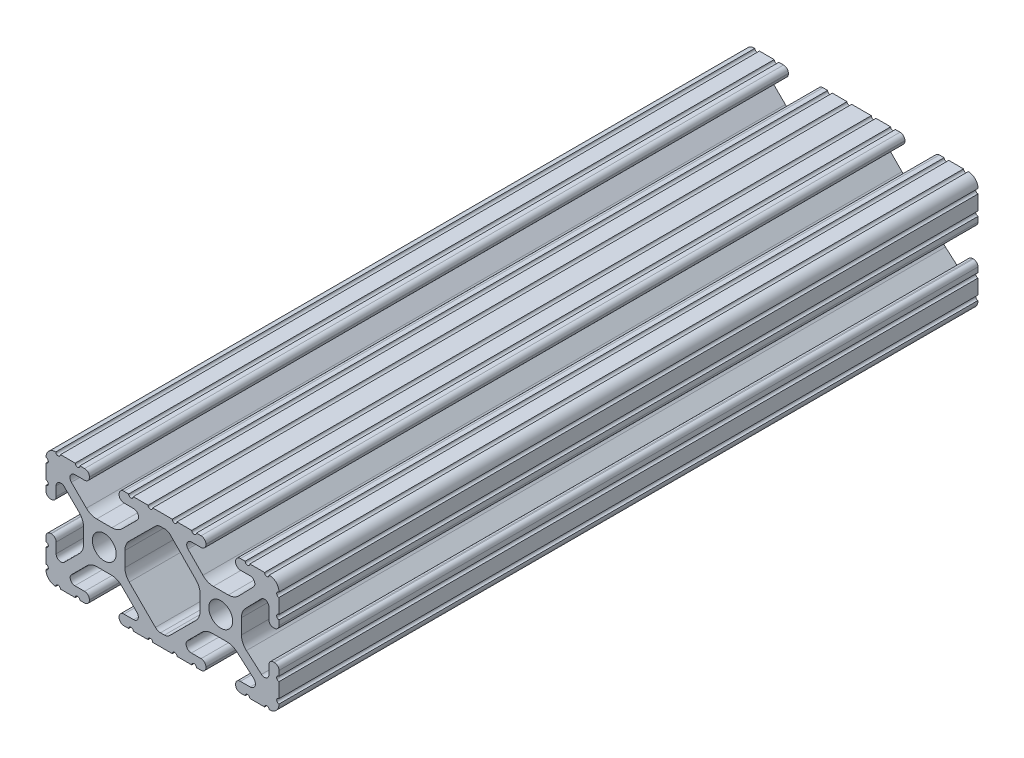
SolidWorks part; units mm, degrees
material "6061-T6 (SS)"
ref_plane "Front Plane" through (0, 0, 0) normal (0, 0, 1) x (1, 0, 0)
ref_plane "Top Plane" through (0, 0, 0) normal (0, 1, 0) x (1, 0, 0)
ref_plane "Right Plane" through (0, 0, 0) normal (1, 0, 0) x (0, 0, -1)
sketch "Sketch1" plane through (0, 0, 0) normal (0, 0, 1) x (1, 0, 0)
  line L0 (-7.2595, -3.8694) -> (-1.5457, -9.5728)
  line L1 (-8.1915, 1.6223) -> (-8.1915, -1.6223)
  line L2 (-1.504, 9.5765) -> (-7.252, 3.8768)
  line L3 (0.5515, 10.033) -> (-0.3952, 10.033)
  line L4 (7.2829, 3.8459) -> (1.6756, 9.5611)
  line L5 (8.1915, -1.6223) -> (8.1915, 1.6223)
  line L6 (1.5457, -9.5728) -> (7.2595, -3.8694)
  line L7 (-0.4332, -10.033) -> (0.4332, -10.033)
  line L8 (18.0171, 12.7) -> (16.9875, 12.7)
  line L9 (15.9385, 11.651) -> (15.9385, 11.5392)
  line L10 (16.9875, 10.4902) -> (19.1164, 10.4902)
  line L11 (19.8441, 8.7652) -> (16.619, 5.4551)
  line L12 (14.3449, 4.4958) -> (11.0833, 4.4958)
  line L13 (8.817, 5.4472) -> (5.5642, 8.7627)
  line L14 (6.2894, 10.4902) -> (8.4125, 10.4902)
  line L15 (9.4615, 11.5392) -> (9.4615, 11.651)
  line L16 (8.4125, 12.7) -> (7.3829, 12.7)
  line L17 (6.3669, 12.7) -> (3.1496, 12.7)
  line L18 (2.1336, 12.7) -> (-2.1336, 12.7)
  line L19 (-3.1496, 12.7) -> (-6.3669, 12.7)
  line L20 (-7.3829, 12.7) -> (-8.4125, 12.7)
  line L21 (-9.4615, 11.651) -> (-9.4615, 11.5392)
  line L22 (-8.4125, 10.4902) -> (-6.2836, 10.4902)
  line L23 (-5.5326, 8.6661) -> (-8.81, 5.4163)
  line L24 (-11.0455, 4.4958) -> (-14.3545, 4.4958)
  line L25 (-16.59, 5.4163) -> (-19.8674, 8.6661)
  line L26 (-19.1164, 10.4902) -> (-16.9875, 10.4902)
  line L27 (-15.9385, 11.5392) -> (-15.9385, 11.651)
  line L28 (-16.9875, 12.7) -> (-18.0171, 12.7)
  line L29 (-19.0331, 12.7) -> (-22.2504, 12.7)
  line L30 (-25.4, 9.5504) -> (-25.4, 6.3331)
  line L31 (-25.4, 5.3171) -> (-25.4, 4.2375)
  line L32 (-24.401, 3.2385) -> (-24.2392, 3.2385)
  line L33 (-23.1902, 4.2875) -> (-23.1902, 6.3347)
  line L34 (-21.434, 7.0665) -> (-18.148, 3.8082)
  line L35 (-17.2085, 1.5536) -> (-17.2085, -1.6952)
  line L36 (-18.1405, -3.9423) -> (-21.4316, -7.2274)
  line L37 (-23.1902, -6.498) -> (-23.1902, -4.2875)
  line L38 (-24.2392, -3.2385) -> (-24.351, -3.2385)
  line L39 (-25.4, -4.2875) -> (-25.4, -5.3171)
  line L40 (-25.4, -6.3331) -> (-25.4, -9.5504)
  line L41 (-22.2504, -12.7) -> (-19.0331, -12.7)
  line L42 (-18.0171, -12.7) -> (-16.9875, -12.7)
  line L43 (-15.9384, -11.651) -> (-15.9384, -11.5392)
  line L44 (-16.9875, -10.4902) -> (-19.1164, -10.4902)
  line L45 (-19.8341, -8.7551) -> (-16.4966, -5.4237)
  line L46 (-14.2536, -4.4958) -> (-11.1464, -4.4958)
  line L47 (-8.9034, -5.4237) -> (-5.5659, -8.7551)
  line L48 (-6.2836, -10.4902) -> (-8.4125, -10.4902)
  line L49 (-9.4616, -11.5392) -> (-9.4616, -11.651)
  line L50 (-8.4125, -12.7) -> (-7.3829, -12.7)
  line L51 (-6.3669, -12.7) -> (-3.1496, -12.7)
  line L52 (-2.1336, -12.7) -> (2.1336, -12.7)
  line L53 (3.1496, -12.7) -> (6.3669, -12.7)
  line L54 (7.3829, -12.7) -> (8.4125, -12.7)
  line L55 (9.4616, -11.651) -> (9.4616, -11.5392)
  line L56 (8.4125, -10.4902) -> (6.2894, -10.4902)
  line L57 (5.4807, -8.5353) -> (8.5979, -5.4237)
  line L58 (10.8409, -4.4958) -> (14.1026, -4.4958)
  line L59 (16.1879, -5.2766) -> (19.8682, -8.4822)
  line L60 (19.1164, -10.4902) -> (16.9875, -10.4902)
  line L61 (15.9384, -11.5392) -> (15.9384, -11.651)
  line L62 (16.9875, -12.7) -> (18.0171, -12.7)
  line L63 (19.0331, -12.7) -> (22.2504, -12.7)
  line L64 (25.4, -9.5504) -> (25.4, -6.3331)
  line L65 (25.4, -5.3171) -> (25.4, -4.2375)
  line L66 (24.401, -3.2385) -> (24.1892, -3.2385)
  line L67 (23.1902, -4.2375) -> (23.1902, -6.1559)
  line L68 (21.584, -6.8869) -> (18.2982, -4.025)
  line L69 (17.2085, -1.6308) -> (17.2085, 1.6308)
  line L70 (18.1094, 3.8465) -> (21.5263, 7.3534)
  line L71 (23.1902, 6.6769) -> (23.1902, 4.2375)
  line L72 (24.1892, 3.2385) -> (24.401, 3.2385)
  line L73 (25.4, 4.2375) -> (25.4, 5.3171)
  line L74 (25.4, 6.3332) -> (25.4, 9.5504)
  line L75 (22.2504, 12.7) -> (19.0331, 12.7)
  circle A0 centre (-12.7, 0) radius 2.6035
  circle A1 centre (12.7, 0) radius 2.6035
  arc A2 (-1.5457, -9.5728) -> (-0.4332, -10.033) centre (-0.4332, -8.4582) ccw
  arc A3 (-8.1915, -1.6223) -> (-7.2595, -3.8694) centre (-5.0165, -1.6223) ccw
  arc A4 (-7.252, 3.8768) -> (-8.1915, 1.6223) centre (-5.0165, 1.6223) ccw
  arc A5 (-0.3952, 10.033) -> (-1.504, 9.5765) centre (-0.3952, 8.4582) ccw
  arc A6 (1.6756, 9.5611) -> (0.5515, 10.033) centre (0.5515, 8.4582) ccw
  arc A7 (8.1915, 1.6223) -> (7.2829, 3.8459) centre (5.0165, 1.6223) ccw
  arc A8 (7.2595, -3.8694) -> (8.1915, -1.6223) centre (5.0165, -1.6223) ccw
  arc A9 (0.4332, -10.033) -> (1.5457, -9.5728) centre (0.4332, -8.4582) ccw
  arc A10 (18.0171, 12.7) -> (19.0331, 12.7) centre (18.5251, 12.7) ccw
  arc A11 (16.9875, 12.7) -> (15.9385, 11.651) centre (16.9875, 11.651) ccw
  arc A12 (15.9385, 11.5392) -> (16.9875, 10.4902) centre (16.9875, 11.5392) ccw
  arc A13 (19.8441, 8.7652) -> (19.1164, 10.4902) centre (19.1164, 9.4742) ccw
  arc A14 (14.3449, 4.4958) -> (16.619, 5.4551) centre (14.3449, 7.6708) ccw
  arc A15 (8.817, 5.4472) -> (11.0833, 4.4958) centre (11.0833, 7.6708) ccw
  arc A16 (6.2894, 10.4902) -> (5.5642, 8.7627) centre (6.2894, 9.4742) ccw
  arc A17 (8.4125, 10.4902) -> (9.4615, 11.5392) centre (8.4125, 11.5392) ccw
  arc A18 (9.4615, 11.651) -> (8.4125, 12.7) centre (8.4125, 11.651) ccw
  arc A19 (6.3669, 12.7) -> (7.3829, 12.7) centre (6.8749, 12.7) ccw
  arc A20 (2.1336, 12.7) -> (3.1496, 12.7) centre (2.6416, 12.7) ccw
  arc A21 (-3.1496, 12.7) -> (-2.1336, 12.7) centre (-2.6416, 12.7) ccw
  arc A22 (-7.3829, 12.7) -> (-6.3669, 12.7) centre (-6.8749, 12.7) ccw
  arc A23 (-8.4125, 12.7) -> (-9.4615, 11.651) centre (-8.4125, 11.651) ccw
  arc A24 (-9.4615, 11.5392) -> (-8.4125, 10.4902) centre (-8.4125, 11.5392) ccw
  arc A25 (-5.5326, 8.6661) -> (-6.2836, 10.4902) centre (-6.2836, 9.4235) ccw
  arc A26 (-11.0455, 4.4958) -> (-8.81, 5.4163) centre (-11.0455, 7.6708) ccw
  arc A27 (-16.59, 5.4163) -> (-14.3545, 4.4958) centre (-14.3545, 7.6708) ccw
  arc A28 (-19.1164, 10.4902) -> (-19.8674, 8.6661) centre (-19.1164, 9.4235) ccw
  arc A29 (-16.9875, 10.4902) -> (-15.9385, 11.5392) centre (-16.9875, 11.5392) ccw
  arc A30 (-15.9385, 11.651) -> (-16.9875, 12.7) centre (-16.9875, 11.651) ccw
  arc A31 (-19.0331, 12.7) -> (-18.0171, 12.7) centre (-18.5251, 12.7) ccw
  arc A32 (-23.2664, 12.6998) -> (-22.2504, 12.7) centre (-22.7584, 12.7) ccw
  arc A33 (-23.2664, 12.6998) -> (-25.3998, 10.5664) centre (-23.2918, 10.5918) ccw
  arc A34 (-25.4, 9.5504) -> (-25.3998, 10.5664) centre (-25.4, 10.0584) ccw
  arc A35 (-25.4, 5.3171) -> (-25.4, 6.3331) centre (-25.4, 5.8251) ccw
  arc A36 (-25.4, 4.2375) -> (-24.401, 3.2385) centre (-24.401, 4.2375) ccw
  arc A37 (-24.2392, 3.2385) -> (-23.1902, 4.2875) centre (-24.2392, 4.2875) ccw
  arc A38 (-21.434, 7.0665) -> (-23.1902, 6.3347) centre (-22.1596, 6.3347) ccw
  arc A39 (-17.2085, 1.5536) -> (-18.148, 3.8082) centre (-20.3835, 1.5536) ccw
  arc A40 (-18.1405, -3.9423) -> (-17.2085, -1.6952) centre (-20.3835, -1.6952) ccw
  arc A41 (-23.1902, -6.498) -> (-21.4316, -7.2274) centre (-22.1596, -6.498) ccw
  arc A42 (-23.1902, -4.2875) -> (-24.2392, -3.2385) centre (-24.2392, -4.2875) ccw
  arc A43 (-24.351, -3.2385) -> (-25.4, -4.2875) centre (-24.351, -4.2875) ccw
  arc A44 (-25.4, -6.3331) -> (-25.4, -5.3171) centre (-25.4, -5.8251) ccw
  arc A45 (-25.3998, -10.5664) -> (-25.4, -9.5504) centre (-25.4, -10.0584) ccw
  arc A46 (-25.3998, -10.5664) -> (-23.2664, -12.6998) centre (-23.2918, -10.5918) ccw
  arc A47 (-22.2504, -12.7) -> (-23.2664, -12.6998) centre (-22.7584, -12.7) ccw
  arc A48 (-18.0171, -12.7) -> (-19.0331, -12.7) centre (-18.5251, -12.7) ccw
  arc A49 (-16.9875, -12.7) -> (-15.9384, -11.651) centre (-16.9875, -11.651) ccw
  arc A50 (-15.9384, -11.5392) -> (-16.9875, -10.4902) centre (-16.9875, -11.5392) ccw
  arc A51 (-19.8341, -8.7551) -> (-19.1164, -10.4902) centre (-19.1164, -9.4742) ccw
  arc A52 (-14.2536, -4.4958) -> (-16.4966, -5.4237) centre (-14.2536, -7.6708) ccw
  arc A53 (-8.9034, -5.4237) -> (-11.1464, -4.4958) centre (-11.1464, -7.6708) ccw
  arc A54 (-6.2836, -10.4902) -> (-5.5659, -8.7551) centre (-6.2836, -9.4742) ccw
  arc A55 (-8.4125, -10.4902) -> (-9.4616, -11.5392) centre (-8.4125, -11.5392) ccw
  arc A56 (-9.4616, -11.651) -> (-8.4125, -12.7) centre (-8.4125, -11.651) ccw
  arc A57 (-6.3669, -12.7) -> (-7.3829, -12.7) centre (-6.8749, -12.7) ccw
  arc A58 (-2.1336, -12.7) -> (-3.1496, -12.7) centre (-2.6416, -12.7) ccw
  arc A59 (3.1496, -12.7) -> (2.1336, -12.7) centre (2.6416, -12.7) ccw
  arc A60 (7.3829, -12.7) -> (6.3669, -12.7) centre (6.8749, -12.7) ccw
  arc A61 (8.4125, -12.7) -> (9.4616, -11.651) centre (8.4125, -11.651) ccw
  arc A62 (9.4616, -11.5392) -> (8.4125, -10.4902) centre (8.4125, -11.5392) ccw
  arc A63 (5.4807, -8.5353) -> (6.2894, -10.4902) centre (6.2894, -9.3455) ccw
  arc A64 (10.8409, -4.4958) -> (8.5979, -5.4237) centre (10.8409, -7.6708) ccw
  arc A65 (16.1879, -5.2766) -> (14.1026, -4.4958) centre (14.1026, -7.6708) ccw
  arc A66 (19.1164, -10.4902) -> (19.8682, -8.4822) centre (19.1164, -9.3455) ccw
  arc A67 (16.9875, -10.4902) -> (15.9384, -11.5392) centre (16.9875, -11.5392) ccw
  arc A68 (15.9384, -11.651) -> (16.9875, -12.7) centre (16.9875, -11.651) ccw
  arc A69 (19.0331, -12.7) -> (18.0171, -12.7) centre (18.5251, -12.7) ccw
  arc A70 (23.2664, -12.6998) -> (22.2504, -12.7) centre (22.7584, -12.7) ccw
  arc A71 (23.2664, -12.6998) -> (25.3998, -10.5664) centre (23.2918, -10.5918) ccw
  arc A72 (25.4, -9.5504) -> (25.3998, -10.5664) centre (25.4, -10.0584) ccw
  arc A73 (25.4, -5.3171) -> (25.4, -6.3331) centre (25.4, -5.8251) ccw
  arc A74 (25.4, -4.2375) -> (24.401, -3.2385) centre (24.401, -4.2375) ccw
  arc A75 (24.1892, -3.2385) -> (23.1902, -4.2375) centre (24.1892, -4.2375) ccw
  arc A76 (21.584, -6.8869) -> (23.1902, -6.1559) centre (22.2207, -6.1559) ccw
  arc A77 (17.2085, -1.6308) -> (18.2982, -4.025) centre (20.3835, -1.6308) ccw
  arc A78 (18.1094, 3.8465) -> (17.2085, 1.6308) centre (20.3835, 1.6308) ccw
  arc A79 (23.1902, 6.6769) -> (21.5263, 7.3534) centre (22.2207, 6.6769) ccw
  arc A80 (23.1902, 4.2375) -> (24.1892, 3.2385) centre (24.1892, 4.2375) ccw
  arc A81 (24.401, 3.2385) -> (25.4, 4.2375) centre (24.401, 4.2375) ccw
  arc A82 (25.4, 6.3332) -> (25.4, 5.3171) centre (25.4, 5.8251) ccw
  arc A83 (25.3998, 10.5664) -> (25.4, 9.5504) centre (25.4, 10.0584) ccw
  arc A84 (25.3998, 10.5664) -> (23.2664, 12.6998) centre (23.2918, 10.5918) ccw
  arc A85 (22.2504, 12.7) -> (23.2664, 12.6998) centre (22.7584, 12.7) ccw
  point P248 (0, 10.033)
extrude "Boss-Extrude1" add sketch "Sketch1" along normal mid plane 152.4
sketch "Sketch2" plane through (0, 12.7, 0) normal (0, 1, 0) x (1, 0, 0)
  line L0 (0, 76.2) -> (0.5515, -76.2) construction
  line L1 (2.1336, 76.2) -> (-2.1336, 76.2) construction
  line L2 (25.3998, 0) -> (-25.3998, 0) construction
  line L4 (25.3998, -76.2) -> (25.3998, 76.2) construction
  line L5 (-25.3998, -76.2) -> (-25.3998, 76.2) construction
  point P5 (0, 0)
  point P9 (-25.3998, 0)
  point P11 (25.3998, 0)
  point P14 (0, 0)
sketch "Sketch3" plane through (-25.4, 0, 0) normal (-1, 0, 0) x (0, 0, 1)
  line L0 (-76.2, -7.9418) -> (-76.2, 7.9417) construction
  line L1 (-76.2, -6.3331) -> (-76.2, -9.5504) construction
  line L2 (-76.2, 9.5504) -> (-76.2, 6.3331) construction
  line L3 (76.2, -7.9418) -> (76.2, 7.9417) construction
  line L4 (76.2, -6.3331) -> (76.2, -9.5504) construction
  line L5 (76.2, 9.5504) -> (76.2, 6.3331) construction
  line L6 (76.2, 0) -> (-76.2, 0) construction
sketch "Sketch4" plane through (25.4, 0, 0) normal (1, 0, 0) x (0, 0, -1)
  line L0 (76.2, 7.9418) -> (76.2, -7.9417) construction
  line L1 (76.2, 6.3332) -> (76.2, 9.5504) construction
  line L2 (76.2, -9.5504) -> (76.2, -6.3331) construction
  line L3 (-76.2, 7.9418) -> (-76.2, -7.9417) construction
  line L4 (-76.2, 6.3332) -> (-76.2, 9.5504) construction
  line L5 (-76.2, -9.5504) -> (-76.2, -6.3331) construction
  line L6 (-76.2, 0) -> (76.2, 0) construction
